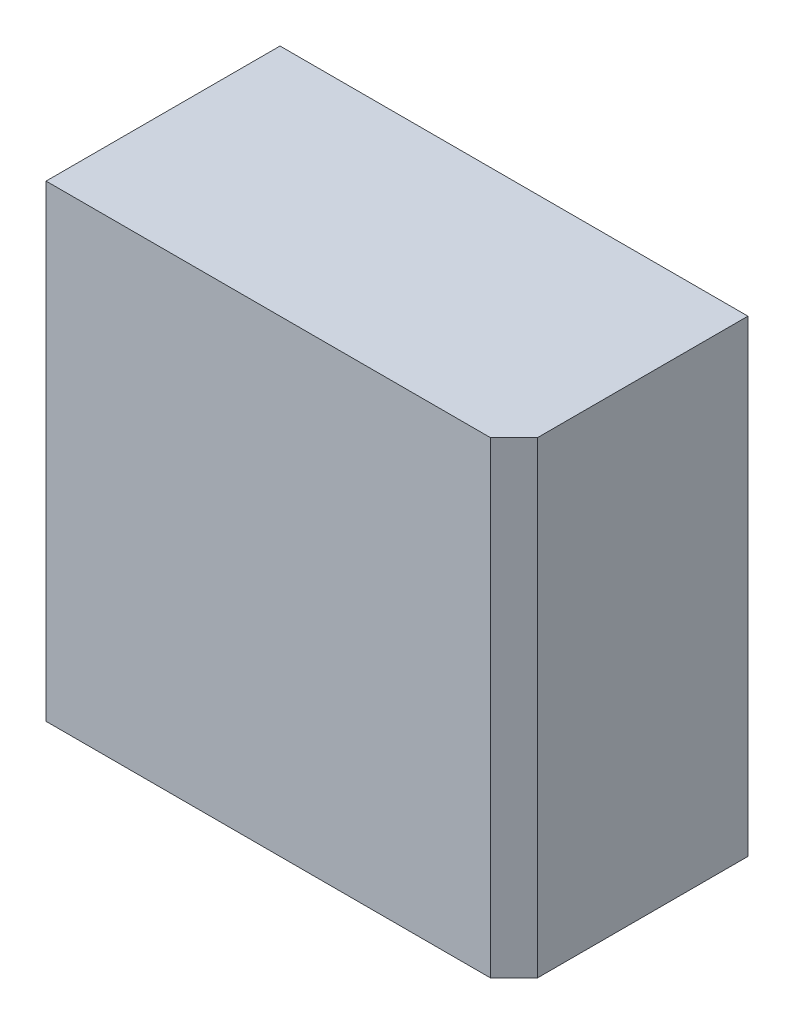
SolidWorks part; units mm, degrees
ref_plane "Ebene vorne" through (0, 0, 0) normal (0, 0, 1) x (1, 0, 0)
ref_plane "Ebene oben" through (0, 0, 0) normal (0, 1, 0) x (1, 0, 0)
ref_plane "Ebene rechts" through (0, 0, 0) normal (1, 0, 0) x (0, 0, -1)
sketch "Skizze1" plane through (0, 0, 0) normal (0, 0, 1) x (1, 0, 0)
  line L1 (50, -50) -> (-50, -50)
  line L2 (50, -50) -> (50, 50)
  line L3 (50, 50) -> (-50, 50)
  line L4 (-50, -50) -> (-50, 50)
  line L5 (50, -50) -> (-50, 50) construction
  line L6 (50, 50) -> (-50, -50) construction
  point P0 (0, 0)
  dimension "D1" = 100
  dimension "D2" = 100
extrude "Aufsatz-Linear austragen1" add sketch "Skizze1" along normal blind 50
chamfer "Fase1" distance 5 angle 45 1 edges at (50, 0, 50)
